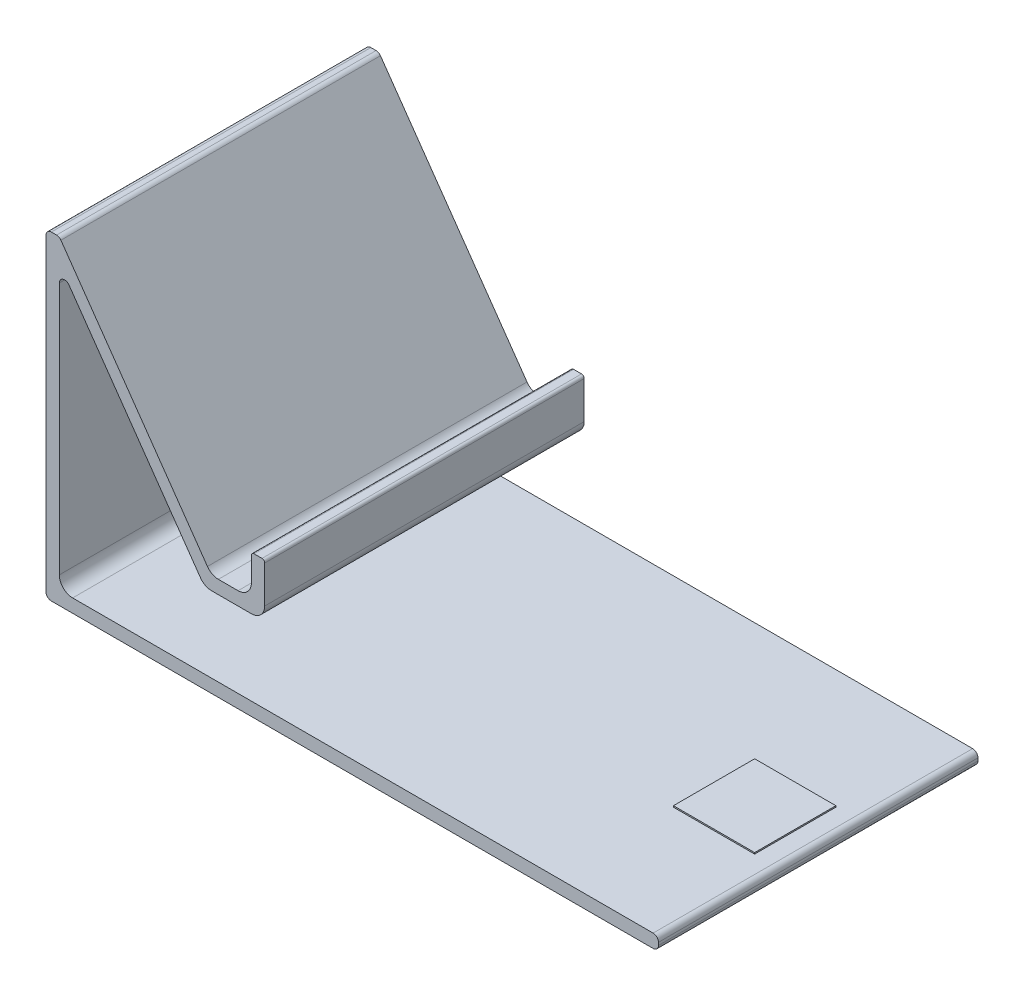
SolidWorks part; units mm, degrees
ref_plane "Front Plane" through (0, 0, 0) normal (0, 0, 1) x (1, 0, 0)
ref_plane "Top Plane" through (0, 0, 0) normal (0, 1, 0) x (1, 0, 0)
ref_plane "Right Plane" through (0, 0, 0) normal (1, 0, 0) x (0, 0, -1)
sketch "Sketch1" plane through (0, 0, 0) normal (0, 0, 1) x (1, 0, 0)
  line L0 (2, 0) -> (228, 0)
  line L1 (0, 2) -> (0, 118)
  line L2 (84.0014, 0) -> (0, 0)
  line L3 (230, 2) -> (230, 3)
  line L4 (228, 5) -> (10, 5)
  line L5 (5, 10) -> (5, 104.9396)
  line L6 (8.6383, 106.0867) -> (58.0283, 35.5504)
  line L7 (62.1241, 33.4183) -> (77.1241, 33.4183)
  line L8 (82.1241, 38.4183) -> (82.1241, 52.4183)
  line L9 (81.1241, 53.4183) -> (78.1241, 53.4183)
  line L10 (77.1241, 52.4183) -> (77.1241, 43.4183)
  line L11 (72.1241, 38.4183) -> (64.7269, 38.4183)
  line L12 (60.6312, 40.5504) -> (5.5972, 119.1472)
  line L13 (2, 120) -> (3.9589, 120)
  arc A0 (5, 104.9396) -> (8.6383, 106.0867) centre (7, 104.9396) cw
  arc A1 (58.0283, 35.5504) -> (62.1241, 33.4183) centre (62.1241, 38.4183) ccw
  arc A2 (77.1241, 33.4183) -> (82.1241, 38.4183) centre (77.1241, 38.4183) ccw
  arc A3 (77.1241, 43.4183) -> (72.1241, 38.4183) centre (72.1241, 43.4183) cw
  arc A4 (64.7269, 38.4183) -> (60.6312, 40.5504) centre (64.7269, 43.4183) cw
  arc A5 (10, 5) -> (5, 10) centre (10, 10) cw
  arc A6 (82.1241, 52.4183) -> (81.1241, 53.4183) centre (81.1241, 52.4183) ccw
  arc A7 (78.1241, 53.4183) -> (77.1241, 52.4183) centre (78.1241, 52.4183) ccw
  arc A8 (228, 0) -> (230, 2) centre (228, 2) ccw
  arc A9 (230, 3) -> (228, 5) centre (228, 3) ccw
  arc A10 (0, 118) -> (2, 120) centre (2, 118) cw
  arc A11 (2, 0) -> (0, 2) centre (2, 2) cw
  arc A12 (5.5972, 119.1472) -> (3.9589, 120) centre (3.9589, 118) ccw
  point P3 (84.0014, 0)
  point P24 (77.1241, 38.4183)
  point P27 (62.1241, 38.4183)
  point P35 (77.1241, 53.4183)
  point P38 (230, 0)
  point P41 (230, 5)
  point P44 (0, 120)
  point P50 (5, 120)
  dimension "D12" = 2
  dimension "D13" = 5
  dimension "D14" = 1
  dimension "D15" = 2
  dimension "D16" = 2
  dimension "D1" = 230
  dimension "D2" = 120
  dimension "D3" = 5
  dimension "D4" = 5
  dimension "D5" = 5
  dimension "D6" = 5
  dimension "D7" = 5
  dimension "D8" = 5
  dimension "D9" = 15
  dimension "D10" = 15
  dimension "D11" = 35
extrude "Boss-Extrude1" add sketch "Sketch1" along normal blind 120 contours L12 A12 L13 A10 L1 A11 L0 A8 L3 A9 L4 A5 L5 A0 L6 A1 L7 A2 L8 A6 L9 A7 L10 A3 L11 A4
ref_plane "Plane1" through (10, 0, 0) normal (1, 0, 0) x (0, 0, -1)
sketch "Sketch3" plane through (0, 0, 0) normal (0, 1, 0) x (1, 0, 0)
  line L0 (228, -120) -> (228, 0) construction
  line L1 (210.25, -60) -> (228, -60) construction
  line L3 (205, -120) -> (205, 0) construction
  line L4 (228, -120) -> (10, -120) construction
  line L5 (228, 0) -> (10, 0) construction
  line L6 (5.5972, -60) -> (228, -60) construction
  line L7 (5.5972, -120) -> (5.5972, 0) construction
  line L9 (220, -45) -> (190, -45)
  line L10 (220, -45) -> (220, -75)
  line L11 (220, -75) -> (190, -75)
  line L12 (190, -45) -> (190, -75)
  line L13 (220, -45) -> (190, -75) construction
  line L14 (220, -75) -> (190, -45) construction
  point P0 (205, -60)
  point P2 (210.25, -60)
  point P3 (210.25, -60)
  point P4 (228, -60)
  point P5 (210.25, -60)
  point P18 (205, -60)
  dimension "D1" = 30
  dimension "D2" = 30
extrude "Boss-Extrude2" add sketch "Sketch3" along normal blind 3
sketch "Sketch6" plane through (0, 0, 0) normal (0, 1, 0) x (1, 0, 0)
  line L0 (81.1241, -60) -> (228, -60) construction
  line L1 (81.1241, -120) -> (81.1241, 0) construction
  line L2 (228, -120) -> (228, 0) construction
  line L4 (221.3741, -44.75) -> (190.8741, -44.75)
  line L5 (221.3741, -44.75) -> (221.3741, -75.25)
  line L6 (221.3741, -75.25) -> (190.8741, -75.25)
  line L7 (190.8741, -44.75) -> (190.8741, -75.25)
  line L8 (221.3741, -44.75) -> (190.8741, -75.25) construction
  line L9 (221.3741, -75.25) -> (190.8741, -44.75) construction
  point P6 (206.1241, -60)
  dimension "D1" = 125
  dimension "D2" = 30.5
  dimension "D3" = 30.5
extrude "Boss-Extrude3" add sketch "Sketch6" along normal blind 5.5
